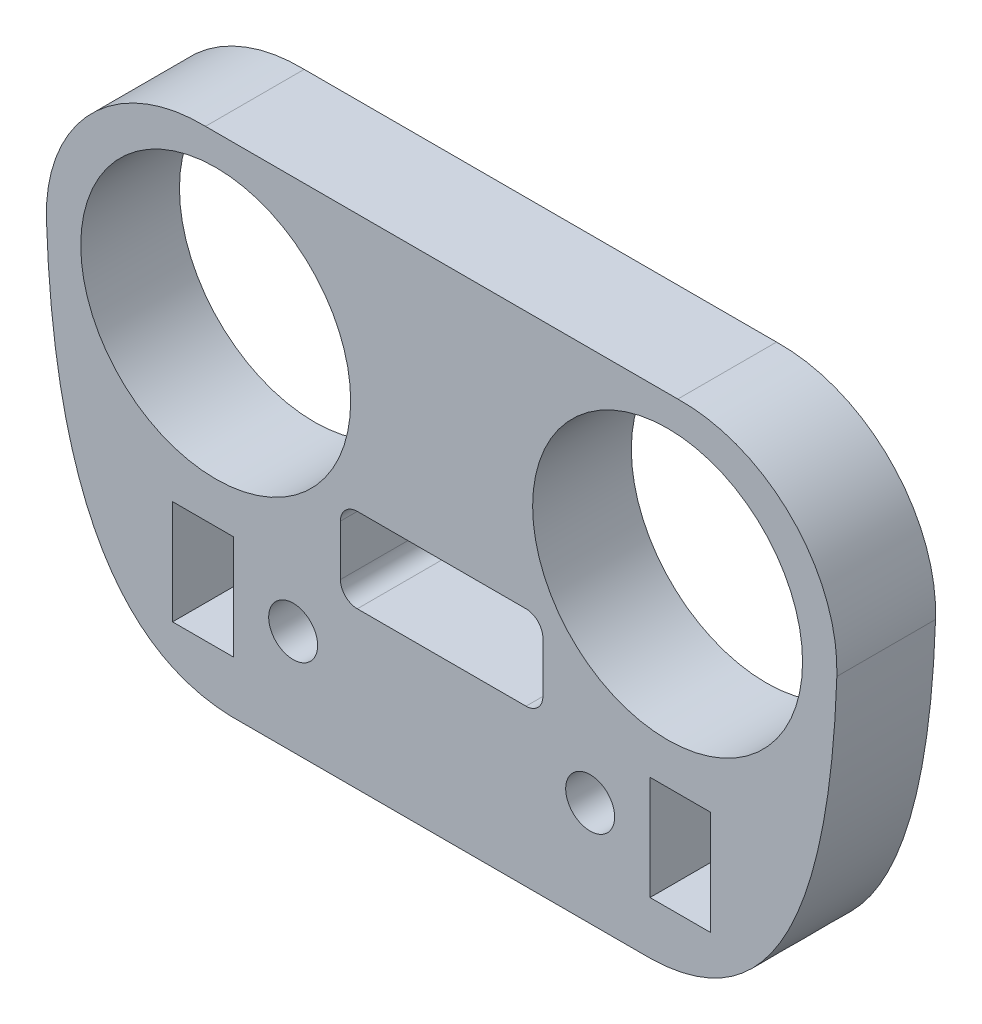
SolidWorks part; units mm, degrees
material "Acrylic (Medium-high impact)"
ref_plane "Front Plane" through (0, 0, 0) normal (0, 0, 1) x (1, 0, 0)
ref_plane "Top Plane" through (0, 0, 0) normal (0, 1, 0) x (1, 0, 0)
ref_plane "Right Plane" through (0, 0, 0) normal (1, 0, 0) x (0, 0, -1)
sketch "Model" plane through (0, 0, 0) normal (0, 0, 1) x (1, 0, 0)
  line L0 (549.6761, 574.3347) -> (554.6761, 574.3347)
  line L1 (554.6761, 576.8347) -> (548.6761, 576.8347) construction
  line L2 (554.6761, 576.8347) -> (560.6761, 576.8347) construction
  line L3 (554.6761, -405.4445) -> (554.6761, 49594.5555) construction
  line L4 (540.6774, 594.6) -> (568.6748, 594.6)
  line L5 (542.1922, 565.0732) -> (567.16, 565.0732)
  line L6 (549.6761, 579.3347) -> (554.6761, 579.3347)
  line L7 (567.0264, 574.3599) -> (567.0264, 568.1865)
  line L8 (570.6264, 574.3599) -> (567.0264, 574.3599)
  line L9 (570.6264, 568.1865) -> (570.6264, 574.3599)
  line L10 (567.0264, 568.1865) -> (570.6264, 568.1865)
  line L11 (560.6761, 578.3347) -> (560.6761, 575.3347)
  line L12 (559.6761, 579.3347) -> (554.6761, 579.3347)
  line L13 (559.6761, 574.3347) -> (554.6761, 574.3347)
  line L14 (538.7258, 571.2732) -> (570.6264, 571.2732) construction
  line L21 (548.6761, 578.3347) -> (548.6761, 575.3347)
  line L32 (542.3258, 568.1865) -> (538.7258, 568.1865)
  line L33 (538.7258, 568.1865) -> (538.7258, 574.3599)
  line L34 (538.7258, 574.3599) -> (542.3258, 574.3599)
  line L35 (542.3258, 574.3599) -> (542.3258, 568.1865)
  circle A0 centre (545.8738, 571.2732) radius 1.4498
  arc A1 (578.1008, 585.0732) -> (568.6748, 594.6) centre (568.8929, 585.3892) ccw
  circle A2 centre (541.284, 584.7975) radius 7.9999
  arc A3 (548.6761, 575.3347) -> (549.6761, 574.3347) centre (549.6761, 575.3347) ccw
  arc A4 (548.6761, 578.3347) -> (549.6761, 579.3347) centre (549.6761, 578.3347) cw
  arc A5 (560.6761, 578.3347) -> (559.6761, 579.3347) centre (559.6761, 578.3347) ccw
  arc A6 (560.6761, 575.3347) -> (559.6761, 574.3347) centre (559.6761, 575.3347) cw
  arc A7 (531.2514, 585.0732) -> (540.6774, 594.6) centre (540.4593, 585.3892) cw
  circle A8 centre (568.0682, 584.7975) radius 7.9999
  circle A9 centre (563.4784, 571.2732) radius 1.4498
  spline S0 degree 2 poles (578.1008, 585.0732) (577.4253, 565.393) (567.16, 565.0732) knots 0 0 0 1 1 1
  spline S48 degree 2 poles (531.2514, 585.0732) (531.9269, 565.393) (542.1922, 565.0732) knots 0 0 0 1 1 1
  point P2 (554.6761, 594.6)
  point P34 (554.6761, 565.0732)
  point P36 (554.6761, 576.8347)
  dimension "D1" = 3.548
  dimension "D2" = 8.8023
  dimension "D3" = 20
  dimension "D4" = 6.1735
  dimension "D5" = 12
  dimension "D6" = 5
  dimension "D7" = 3.6
  dimension "D8" = 29.5268
  dimension "D9" = 6.2
extrude "Boss-Extrude1" add sketch "Model" along normal blind 5.85 contours A7 S48 L5 S0 A1 L4 A9 L11 A6 L13 L0 A3 L21 A4 L6 L12 A5 A2 A0 L10 L7 L8 L9 L34 L35 L32 L33 A8
